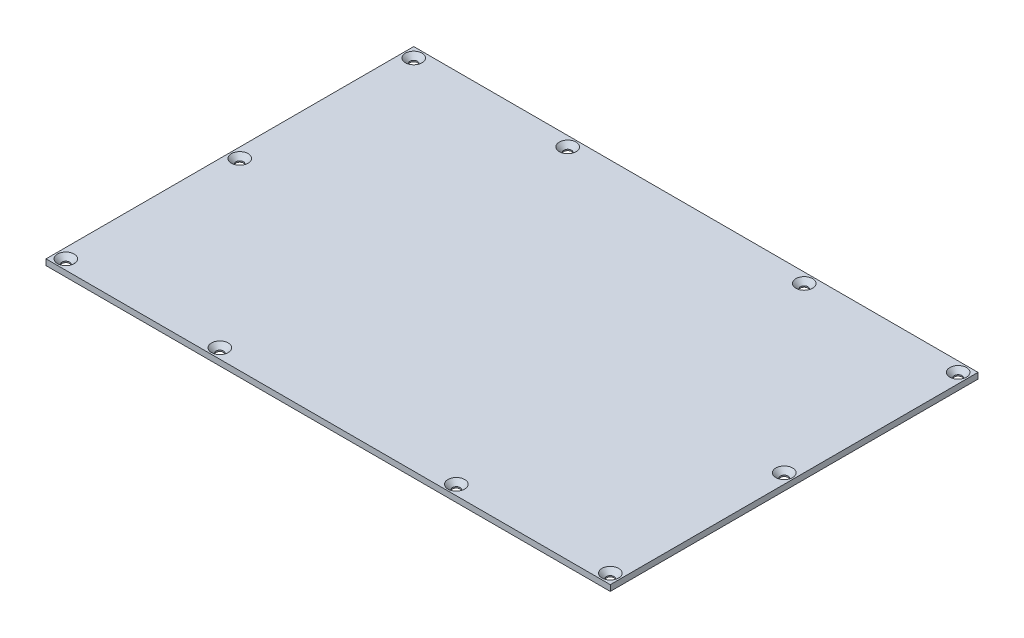
SolidWorks part; units mm, degrees
ref_plane "Front Plane" through (0, 0, 0) normal (0, 0, 1) x (1, 0, 0)
ref_plane "Top Plane" through (0, 0, 0) normal (0, 1, 0) x (1, 0, 0)
ref_plane "Right Plane" through (0, 0, 0) normal (1, 0, 0) x (0, 0, -1)
sketch "Sketch1" plane through (0, 0, 0) normal (0, 1, 0) x (1, 0, 0)
  line L0 (-227.86, -148.48) -> (-227.86, 0)
  line L1 (0, 0) -> (-227.86, 0)
  line L2 (0, -148.48) -> (-227.86, -148.48)
  line L3 (-4, -4) -> (-4, 0) construction
  line L4 (-4, -4) -> (0, -4) construction
  line L5 (-4, -4) -> (-66.18, -4) construction
  line L6 (-66.18, -4) -> (-161.68, -4) construction
  line L7 (0, 0) -> (0, -148.48)
  line L8 (-161.68, -4) -> (-223.86, -4) construction
  line L9 (-223.86, -4) -> (-223.86, -144.48) construction
  line L10 (-223.86, -144.48) -> (-4, -144.48) construction
  line L11 (-4, -144.48) -> (-4, -4) construction
  line L12 (-66.18, -4) -> (-66.18, -144.48) construction
  line L13 (-161.68, -144.48) -> (-161.68, -4) construction
  circle A0 centre (-4, -74.24) radius 1.5
  circle A1 centre (-223.86, -74.24) radius 1.5
  circle A12 centre (-161.68, -144.48) radius 1.5
  circle A13 centre (-66.18, -144.48) radius 1.5
  circle A14 centre (-66.18, -4) radius 1.5
  circle A15 centre (-161.68, -4) radius 1.5
  circle A20 centre (-4, -144.48) radius 1.5
  circle A21 centre (-223.86, -144.48) radius 1.5
  circle A22 centre (-223.86, -4) radius 1.5
  circle A23 centre (-4, -4) radius 1.5
  dimension "D4" = 62.18
  dimension "D1" = 3
  dimension "D2" = 62.18
  dimension "D10" = 3
  dimension "D3" = 95.5
  dimension "D5" = 140.48
  dimension "D6" = 148.48
  dimension "D7" = 227.86
  dimension "D8" = 4
  dimension "D9" = 4
extrude "Boss-Extrude1" add sketch "Sketch1" along normal blind 2.3813
hole_wizard "CSK for M3 Flat Head Machine Screw6" positions "Sketch23" profile "Sketch22" countersink size "M3" standard "Ansi Metric" end condition through all
sketch "Sketch23" plane through (0, 2.3813, 0) normal (0, 1, 0) x (-1, 0, 0)
  point P1 (4, 144.48)
  point P10 (66.18, 144.48)
  point P13 (223.86, 144.48)
  point P22 (161.68, 144.48)
  point P25 (223.86, 4)
  point P34 (161.68, 4)
  point P37 (66.18, 4)
  point P46 (4, 4)
sketch "Sketch22" plane through (-4, 2.3813, 144.48) normal (1, 0, 0) x (0, 0, 1)
  line L0 (0, 0) -> (0, 2.3812)
  line L1 (0, 2.3812) -> (1.5, 2.3812)
  line L2 (1.5, 2.3812) -> (1.5, 1.875)
  line L3 (1.5, 1.875) -> (3.375, 0)
  line L5 (3.375, 0) -> (0, 0)
  line L6 (-1.5, 1.875) -> (-3.375, 0) construction
  line L11 (0, -6.35) -> (0, 107.95) construction
  dimension "Thru Hole Dia." = 3
  dimension "Thru Hole Depth" = 2.3813
  dimension "Near C'Sink Dia." = 6.75
  dimension "Near C'Sink Angle" = 90
hole_wizard "CSK for M3 Flat Head Machine Screw7" positions "Sketch25" profile "Sketch24" countersink size "M3" standard "Ansi Metric" end condition through all
sketch "Sketch25" plane through (0, 2.3813, 0) normal (0, 1, 0) x (-1, 0, 0)
  point P1 (4, 74.24)
  point P4 (223.86, 74.24)
sketch "Sketch24" plane through (-4, 2.3813, 74.24) normal (1, 0, 0) x (0, 0, 1)
  line L0 (0, 0) -> (0, 2.3812)
  line L1 (0, 2.3812) -> (1.5, 2.3812)
  line L2 (1.5, 2.3812) -> (1.5, 1.875)
  line L3 (1.5, 1.875) -> (3.375, 0)
  line L5 (3.375, 0) -> (0, 0)
  line L6 (-1.5, 1.875) -> (-3.375, 0) construction
  line L11 (0, -6.35) -> (0, 107.95) construction
  dimension "Thru Hole Dia." = 3
  dimension "Thru Hole Depth" = 2.3813
  dimension "Near C'Sink Dia." = 6.75
  dimension "Near C'Sink Angle" = 90
